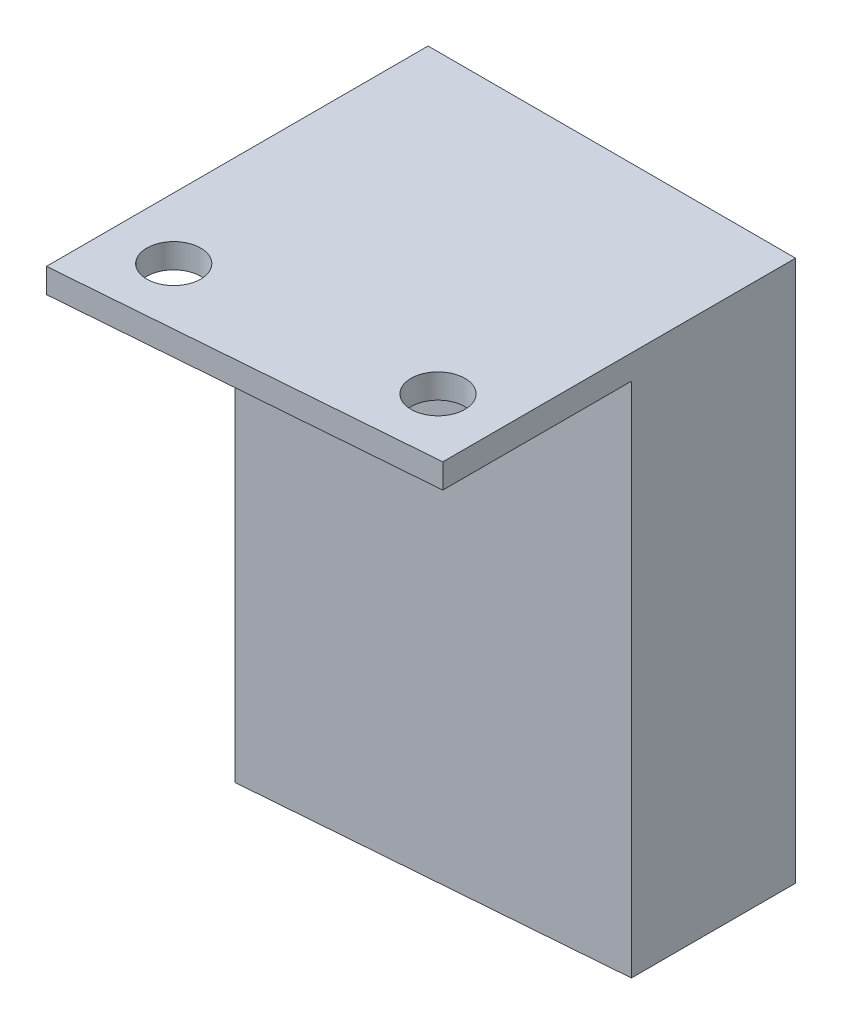
SolidWorks part; units mm, degrees
ref_plane "Front Plane" through (0, 0, 0) normal (0, 0, 1) x (1, 0, 0)
ref_plane "Top Plane" through (0, 0, 0) normal (0, 1, 0) x (1, 0, 0)
ref_plane "Right Plane" through (0, 0, 0) normal (1, 0, 0) x (0, 0, -1)
sketch "Sketch1" plane through (0, 0, 0) normal (0, 0, 1) x (1, 0, 0)
  line L1 (0, 0) -> (38.1, 0)
  line L2 (0, 0) -> (0, 25.4)
  line L3 (0, 25.4) -> (38.1, 25.4)
  line L4 (38.1, 0) -> (38.1, 25.4)
  dimension "D1" = 25.4
  dimension "D2" = 38.1
extrude "Boss-Extrude1" add sketch "Sketch1" along normal blind 17.018
sketch "Sketch4" plane through (0, 25.4, 0) normal (0, 1, 0) x (1, 0, 0)
  line L0 (0, -33.2245) -> (38.1, -30.226) construction
  line L1 (0, -17.018) -> (38.1, -17.018)
  line L2 (0, -17.018) -> (0, -40.386)
  line L3 (0, -40.386) -> (38.1, -40.386)
  line L4 (38.1, -17.018) -> (38.1, -40.386)
  circle A0 centre (6.35, -32.7248) radius 2.794
  circle A1 centre (31.75, -30.7258) radius 2.794
  dimension "D5" = 5.588
  dimension "D6" = 5.588
  dimension "D1" = 38.1
  dimension "D2" = 23.368
  dimension "D3" = 175.5
  dimension "D4" = 10.16
  dimension "D7" = 25.4
  dimension "D8" = 6.35
extrude "Boss-Extrude2" add sketch "Sketch4" against normal blind 2.54
sketch "Sketch5" plane through (0, 25.4, 0) normal (0, 1, 0) x (1, 0, 0)
  line L0 (38.1, -36.576) -> (0, -39.5745)
  line L1 (38.1, -40.386) -> (38.1, 0) construction
  line L2 (0, -40.386) -> (0, 0) construction
  line L3 (0, -40.386) -> (38.1, -40.386) construction
  line L4 (0, -39.5745) -> (0, -40.386)
  line L5 (0, -40.386) -> (38.1, -40.386)
  line L6 (38.1, -40.386) -> (38.1, -36.576)
  dimension "D1" = 85.5
  dimension "D2" = 3.81
extrude "Cut-Extrude1" cut sketch "Sketch5" against normal through all
sketch "Sketch7" plane through (0, 0, 0) normal (0, -1, 0) x (1, 0, 0)
  line L0 (38.1, 17.018) -> (0, 20.0165)
  line L1 (0, 17.018) -> (38.1, 17.018) construction
  line L2 (0, 17.018) -> (0, 20.0165)
  line L3 (0, 17.018) -> (38.1, 17.018)
  dimension "D1" = 4.5
  dimension "D2" = 38.1
extrude "Boss-Extrude3" add sketch "Sketch7" against normal blind 22.86
sketch "Sketch9" plane through (0, 0, 0) normal (0, -1, 0) x (1, 0, 0)
  line L0 (0, 0) -> (38.1, 0)
  line L1 (38.1, 0) -> (38.1, 17.018)
  line L2 (38.1, 17.018) -> (0, 20.0165)
  line L3 (0, 20.0165) -> (0, 0)
sketch "Sketch10" plane through (0, 0, 0) normal (0, -1, 0) x (1, 0, 0)
  line L0 (0, 0) -> (0, 20.0165)
  line L1 (0, 20.0165) -> (38.1, 17.018)
  line L2 (38.1, 17.018) -> (38.1, 0)
  line L3 (38.1, 0) -> (0, 0)
extrude "Boss-Extrude5" add sketch "Sketch10" along normal blind 30.734
sketch "Sketch11" plane through (0, 0, 0) normal (0, 0, -1) x (-1, 0, 0)
  line L0 (0, -30.734) -> (-38.1, -30.734) construction
  line L1 (-38.1, -30.734) -> (-38.1, 25.4) construction
  circle A0 centre (-25.4, -2.794) radius 2.0193
  circle A1 centre (-12.7, -2.794) radius 2.0193
  dimension "D1" = 4.0386
  dimension "D2" = 4.0386
  dimension "D3" = 27.94
  dimension "D4" = 27.94
  dimension "D5" = 12.7
  dimension "D6" = 12.7
extrude "Cut-Extrude3" cut sketch "Sketch11" against normal blind 30.734
extrude "Boss-Extrude4" add sketch "Sketch9" along normal blind 30.734
